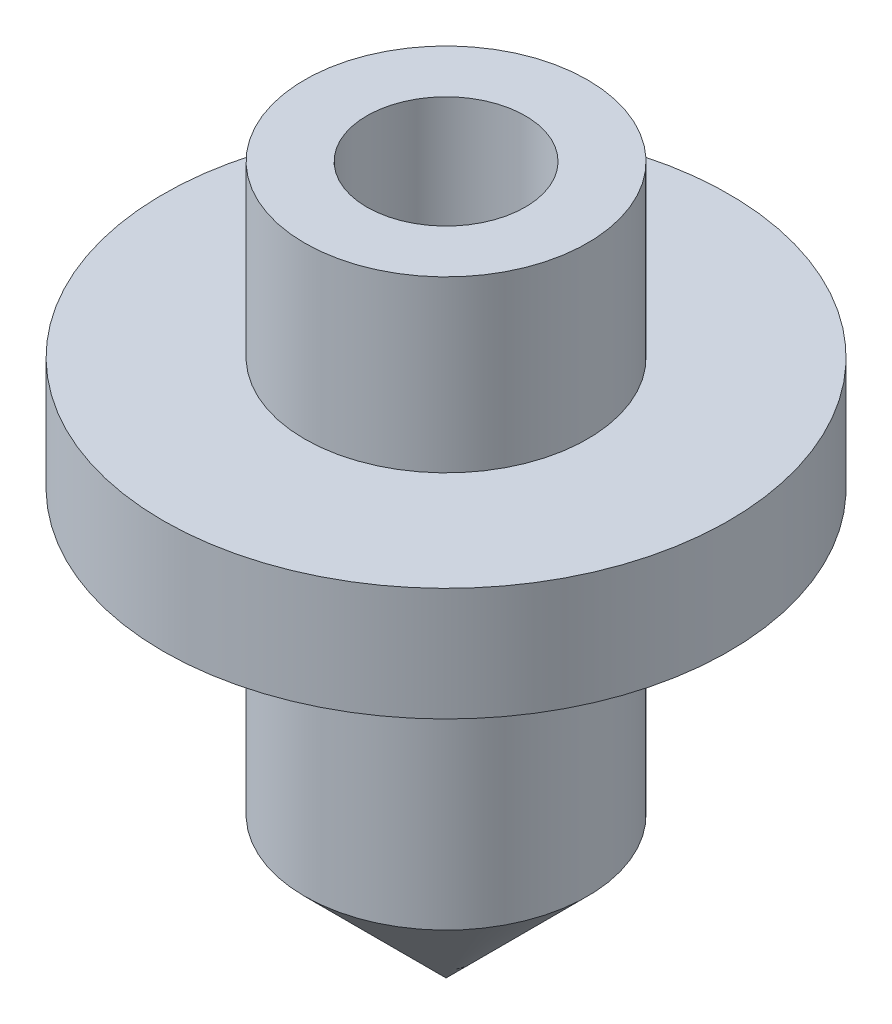
SolidWorks part; units mm, degrees
ref_plane "Front Plane" through (0, 0, 0) normal (0, 0, 1) x (1, 0, 0)
ref_plane "Top Plane" through (0, 0, 0) normal (0, 1, 0) x (1, 0, 0)
ref_plane "Right Plane" through (0, 0, 0) normal (1, 0, 0) x (0, 0, -1)
sketch "Sketch1" plane through (0, 0, 0) normal (1, 0, 0) x (0, 0, -1)
  line L0 (0, 58.139) -> (0, -63.5222) construction
  line L1 (-25, 21.4719) -> (-25, -28.5281)
  line L2 (-25, -28.5281) -> (0, -53.5281)
  line L3 (-25, 21.4719) -> (-50, 21.4719)
  line L4 (-50, 21.4719) -> (-50, 41.4719)
  line L5 (-50, 41.4719) -> (-25, 41.4719)
  line L6 (-25, 41.4719) -> (-25, 71.4719)
  line L7 (-25, 71.4719) -> (-14, 71.4719)
  line L8 (-14, 71.4719) -> (-14, -28.5281)
  line L9 (-14, -28.5281) -> (0, -28.5281)
  line L10 (0, -53.5281) -> (0, -28.5281)
  point P5 (0, 0)
  dimension "D1" = 45
  dimension "D2" = 50
  dimension "D3" = 28
  dimension "D4" = 100
  dimension "D5" = 20
  dimension "D6" = 100
  dimension "D7" = 25
  dimension "D8" = 50
revolve "Revolve1" add sketch "Sketch1" angle 360 about L0
